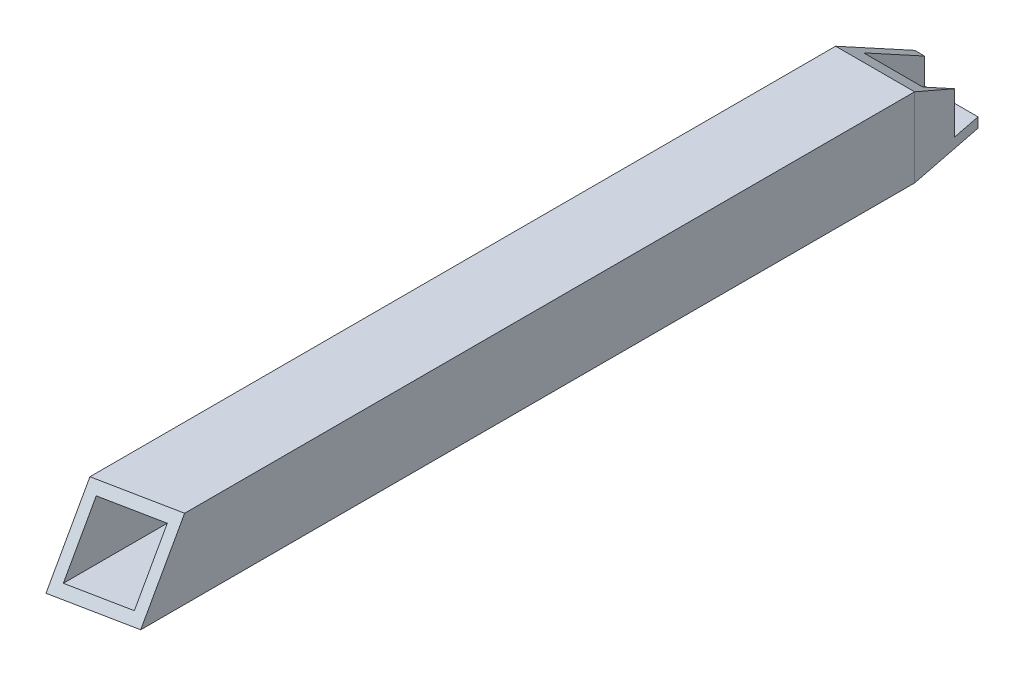
SolidWorks part; units mm, degrees
material "6061 Alloy"
ref_plane "Front Plane" through (0, 0, 0) normal (0, 0, 1) x (1, 0, 0)
ref_plane "Top Plane" through (0, 0, 0) normal (0, 1, 0) x (1, 0, 0)
ref_plane "Right Plane" through (0, 0, 0) normal (1, 0, 0) x (0, 0, -1)
sketch "Sketch1" plane through (0, 0, 0) normal (0, 0, 1) x (1, 0, 0)
  line L0 (12.7, 0) -> (9.525, 0) construction
  line L1 (-12.7, 0) -> (12.7, 0) construction
  line L2 (0, 12.7) -> (0, -12.7)
  point P7 (0, 0)
sketch "Sketch2" plane through (0, 0, 0) normal (1, 0, 0) x (0, 0, -1)
  line L0 (139.7, 0) -> (-139.7, 0)
  point P4 (0, 0)
  dimension "Length" = 279.4
sketch "Sketch3" plane through (0, 0, 0) normal (0, 0, 1) x (1, 0, 0)
  line L0 (-12.7, 0) -> (12.7, 0) construction
  line L5 (12.7, -12.7) -> (-12.7, -12.7)
  line L6 (12.7, -12.7) -> (12.7, 12.7)
  line L11 (12.7, 12.7) -> (-12.7, 12.7)
  line L12 (-12.7, -12.7) -> (-12.7, 12.7)
  line L14 (12.7, -12.7) -> (-12.7, 12.7) construction
  line L15 (12.7, 12.7) -> (-12.7, -12.7) construction
  line L16 (9.525, -9.525) -> (-9.525, -9.525)
  line L17 (9.525, -9.525) -> (9.525, 9.525)
  line L18 (9.525, 9.525) -> (-9.525, 9.525)
  line L19 (-9.525, -9.525) -> (-9.525, 9.525)
  line L20 (9.525, -9.525) -> (-9.525, 9.525) construction
  line L21 (9.525, 9.525) -> (-9.525, -9.525) construction
  point P0 (0, 0)
  point P5 (0, 0)
  point P13 (9.525, -12.7)
  dimension "D1" = 3.175
  dimension "D3" = 25.4
  dimension "D4" = 25.4
extrude "Boss-Extrude1" add sketch "Sketch3" along normal up to vertex (139.7 mm away) and the other way up to vertex (139.7 mm away) up to point (0, 0, 139.7) other way up to point (0, 0, -139.7)
sketch "Sketch5" plane through (0, 0, 0) normal (1, 0, 0) x (0, 0, -1)
  line L0 (-139.7, 0) -> (139.7, 0) construction
  line L3 (-139.7, -12.7) -> (-139.7, 12.7) construction
  line L4 (139.7, -12.7) -> (139.7, 12.7) construction
  point P6 (-111.125, 0)
  point P7 (-101.6, 0)
  point P8 (101.6, 0)
  point P10 (111.125, 0)
  dimension "D1" = 28.575
  dimension "D2" = 38.1
  dimension "D3" = 28.575
  dimension "D4" = 38.1
sketch "Sketch7" plane through (0, -12.7, 0) normal (0, -1, 0) x (1, 0, 0)
  line L0 (-12.7, 139.7) -> (12.7, 134.643) construction
  line L1 (12.7, 139.7) -> (12.7, -139.7) construction
  line L2 (-12.7, 139.7) -> (12.7, 139.7) construction
  dimension "D1" = 11.26
ref_plane "Plane2" through (26.2687, 0, 131.9416) normal (0.1953, 0, 0.9808) x (0, -1, 0)
ref_plane "Plane3" through (19.2031, 53.6419, 96.4523) normal (0.1714, 0.4788, 0.861) x (0.9808, 0, -0.1953)
other "SurfaceCut2"
sketch "Sketch8" plane through (0, -12.7, 0) normal (0, -1, 0) x (1, 0, 0)
  line L0 (12.7, -114.3) -> (7.643, -139.7) construction
  line L1 (12.7, 134.643) -> (12.7, -139.7) construction
  line L2 (-12.7, -139.7) -> (12.7, -139.7) construction
  dimension "D1" = 11.26
  dimension "D2" = 25.4
sketch "Sketch11" plane through (-12.7, 0, 0) normal (-1, 0, 0) x (0, 0, 1)
  line L0 (-139.7, -1.1888) -> (-114.3, 12.7) construction
  line L1 (-139.7, 12.7) -> (-139.7, -12.7) construction
  line L2 (125.5738, 12.7) -> (-139.7, 12.7) construction
  dimension "D1" = 28.67
  dimension "D2" = 25.4
sketch "Sketch9" plane through (0, 0, -139.7) normal (0, 0, -1) x (-1, 0, 0)
  line L0 (-7.643, -12.7) -> (-7.643, 12.7) construction
  line L1 (-12.7, 12.7) -> (12.7, 12.7) construction
  line L2 (12.7, -1.1793) -> (-12.7, -1.1793) construction
  line L3 (12.7, 12.7) -> (12.7, -12.7) construction
  line L4 (-12.7, -12.7) -> (-12.7, 12.7) construction
ref_plane "Plane4" through (34.1046, 0, -6.79) normal (0.9808, 0, -0.1953) x (0, 1, 0)
other "SurfaceCut4"
ref_plane "Plane6" through (0, 57.8179, -31.5364) normal (0, 0.8779, -0.4788) x (1, 0, 0)
other "SurfaceCut5"
equation "\"D1@Sketch3\"=\"Wall thickness@Sketch1\""
equation "\"D1@Sketch5\"=\"Width@Sketch1\"*1.125"
equation "\"D2@Sketch5\"=\"Width@Sketch1\"*1.5"
equation "\"D3@Sketch5\"=\"D1@Sketch5\""
equation "\"D4@Sketch5\"=\"D2@Sketch5\""
equation "\"D2@Sketch3\"=\"Wall Thickness@Sketch1\""
